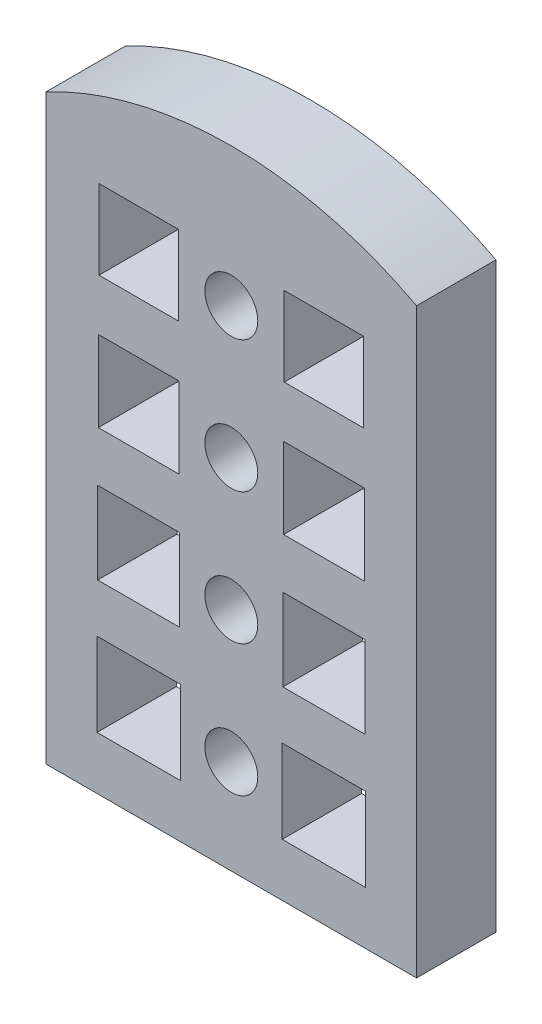
SolidWorks part; units mm, degrees
ref_plane "Plan de face" through (0, 0, 0) normal (0, 0, 1) x (1, 0, 0)
ref_plane "Plan de dessus" through (0, 0, 0) normal (0, 1, 0) x (1, 0, 0)
ref_plane "Plan de droite" through (0, 0, 0) normal (1, 0, 0) x (0, 0, -1)
sketch "Esquisse3" plane through (0, 0, 0) normal (0, 0, 1) x (1, 0, 0)
  line L1 (-87.1617, 41.4948) -> (-59.1617, 41.4948) construction
  line L2 (-87.1617, 41.4948) -> (-87.1617, -2.5052)
  line L3 (-87.1617, -2.5052) -> (-59.1617, -2.5052)
  line L4 (-59.1617, 41.4948) -> (-59.1617, -2.5052)
  arc A0 (-87.1617, 41.4948) -> (-59.1617, 41.4948) centre (-73.1617, 14.9618) cw
  line B0 (-77.1617, 37.4948) -> (-83.1617, 37.4948)
  line B1 (-77.1617, 37.4948) -> (-77.1617, 31.4948)
  line B2 (-77.1617, 31.4948) -> (-83.1617, 31.4948)
  line B3 (-83.1617, 37.4948) -> (-83.1617, 31.4948)
  line B4 (-69.1617, 37.4948) -> (-63.1617, 37.4948)
  line B5 (-69.1617, 37.4948) -> (-69.1617, 31.4948)
  line B6 (-69.1617, 31.4948) -> (-63.1617, 31.4948)
  line B7 (-63.1617, 37.4948) -> (-63.1617, 31.4948)
  line B8 (-73.1617, 34.4948) -> (-73.1617, 38.158) construction
  circle B9 centre (-73.1617, 34.4948) radius 2
  line B10 (-83.1617, 37.4948) -> (-77.1617, 31.4948) construction
  line B11 (-77.1117, 27.5948) -> (-83.2117, 27.5948)
  line B12 (-77.1117, 27.5948) -> (-77.1117, 21.4948)
  line B13 (-77.1117, 21.4948) -> (-83.2117, 21.4948)
  line B14 (-83.2117, 27.5948) -> (-83.2117, 21.4948)
  line B15 (-69.2117, 27.5948) -> (-63.1117, 27.5948)
  line B16 (-69.2117, 27.5948) -> (-69.2117, 21.4948)
  line B17 (-69.2117, 21.4948) -> (-63.1117, 21.4948)
  line B18 (-63.1117, 27.5948) -> (-63.1117, 21.4948)
  line B19 (-73.1617, 24.5448) -> (-73.1617, 28.2164) construction
  circle B20 centre (-73.1617, 24.5448) radius 2
  line B21 (-77.0617, 17.6948) -> (-83.2617, 17.6948)
  line B22 (-77.0617, 17.6948) -> (-77.0617, 11.4948)
  line B23 (-77.0617, 11.4948) -> (-83.2617, 11.4948)
  line B24 (-83.2617, 17.6948) -> (-83.2617, 11.4948)
  line B25 (-69.2617, 17.6948) -> (-63.0617, 17.6948)
  line B26 (-69.2617, 17.6948) -> (-69.2617, 11.4948)
  line B27 (-69.2617, 11.4948) -> (-63.0617, 11.4948)
  line B28 (-63.0617, 17.6948) -> (-63.0617, 11.4948)
  line B29 (-73.1617, 14.5948) -> (-73.1617, 18.2748) construction
  circle B30 centre (-73.1617, 14.5948) radius 2
  line B31 (-77.0117, 7.7948) -> (-83.3117, 7.7948)
  line B32 (-77.0117, 7.7948) -> (-77.0117, 1.4948)
  line B33 (-77.0117, 1.4948) -> (-83.3117, 1.4948)
  line B34 (-83.3117, 7.7948) -> (-83.3117, 1.4948)
  line B35 (-69.3117, 7.7948) -> (-63.0117, 7.7948)
  line B36 (-69.3117, 7.7948) -> (-69.3117, 1.4948)
  line B37 (-69.3117, 1.4948) -> (-63.0117, 1.4948)
  line B38 (-63.0117, 7.7948) -> (-63.0117, 1.4948)
  line B39 (-73.1617, 4.6448) -> (-73.1617, 8.3332) construction
  circle B40 centre (-73.1617, 4.6448) radius 2
  dimension "D7" = 30
  dimension "D1" = 10
  dimension "D2" = 10
  dimension "D3" = 10
  dimension "D4" = 4
  dimension "D5" = 4
  dimension "D6" = 4
sketch_block_instance "Trou M4 plots6 tol0mm-1"
sketch_block "Trou M4 plots6 tol0mm" parameters "D2"=4, "D1"=6, "D3"=6, "D4"=8
sketch_block_instance "Trou M4 plots6 tol0.1mm-1"
sketch_block "Trou M4 plots6 tol0.1mm" parameters "D2"=4, "D1"=6, "D3"=6.1, "D4"=8
sketch_block_instance "Trou M4 plots6 tol0.2mm-1"
sketch_block "Trou M4 plots6 tol0.2mm" parameters "D2"=4, "D1"=6, "D3"=6.2, "D4"=8
sketch_block_instance "Trou M4 plots6 tol0.3mm-1"
sketch_block "Trou M4 plots6 tol0.3mm" parameters "D2"=4, "D1"=6, "D3"=6.3, "D4"=8
extrude "Boss.-Extru.1" add sketch "Esquisse3" along normal blind 6
